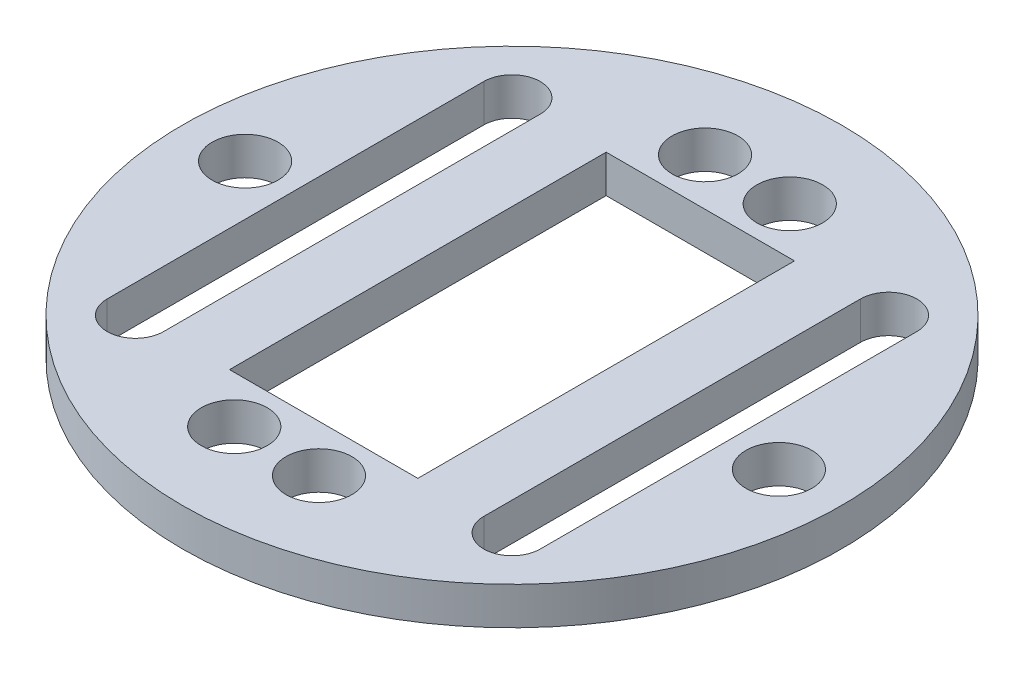
SolidWorks part; units mm, degrees
ref_plane "Front Plane" through (0, 0, 0) normal (0, 0, 1) x (1, 0, 0)
ref_plane "Top Plane" through (0, 0, 0) normal (0, 1, 0) x (1, 0, 0)
ref_plane "Right Plane" through (0, 0, 0) normal (1, 0, 0) x (0, 0, -1)
sketch "Sketch1" plane through (0, 0, 0) normal (0, 1, 0) x (1, 0, 0)
  circle A0 centre (0, 0) radius 35
  dimension "D1" = 70
extrude "Boss-Extrude1" add sketch "Sketch1" along normal blind 4
sketch "Sketch2" plane through (0, 0, 0) normal (0, 1, 0) x (1, 0, 0)
  line L0 (0, 35) -> (0, 20) construction
  line L1 (-35, 0) -> (0, 0) construction
  line L2 (-10, -20) -> (-10, 20)
  line L3 (-10, -20) -> (10, -20)
  line L5 (-10, 20) -> (10, 20)
  line L6 (10, -20) -> (10, 20)
  line L7 (-4.5, 20) -> (-4.5, 25) construction
  line L8 (-20, 20) -> (-20, -20) construction
  line L9 (-17, 20) -> (-17, -20)
  line L10 (-23, 20) -> (-23, -20)
  line L11 (20, 20) -> (20, -20) construction
  line L12 (17, 20) -> (17, -20)
  line L13 (23, 20) -> (23, -20)
  line L14 (0, -20) -> (0, -35) construction
  line L15 (10, 0) -> (35, 0) construction
  circle A0 centre (0, 0) radius 35 construction
  circle A1 centre (-4.5, 25) radius 3.5
  circle A2 centre (4.5, 25) radius 3.5
  circle A3 centre (4.5, -25) radius 3.5
  circle A4 centre (-4.5, -25) radius 3.5
  circle A5 centre (-28.3467, 0) radius 3.5
  arc A6 (-17, 20) -> (-23, 20) centre (-20, 20) ccw
  arc A7 (-23, -20) -> (-17, -20) centre (-20, -20) ccw
  circle A8 centre (28.3467, 0) radius 3.5
  arc A9 (17, 20) -> (23, 20) centre (20, 20) cw
  arc A10 (23, -20) -> (17, -20) centre (20, -20) cw
  point P26 (-20, 0)
  point P35 (20, 0)
  dimension "D6" = 7
  dimension "D7" = 7
  dimension "D8" = 3
  dimension "D1" = 40
  dimension "D2" = 20
  dimension "D4" = 5
  dimension "D5" = 4.5
  dimension "D9" = 12
extrude "Cut-Extrude1" cut sketch "Sketch2" along normal blind 5 contours L9 A7 L10 A6 | A5 | L2 L5 L6 L3 | L12 A10 L13 A9 | A8 | A4 | A3 | A1 | A2
